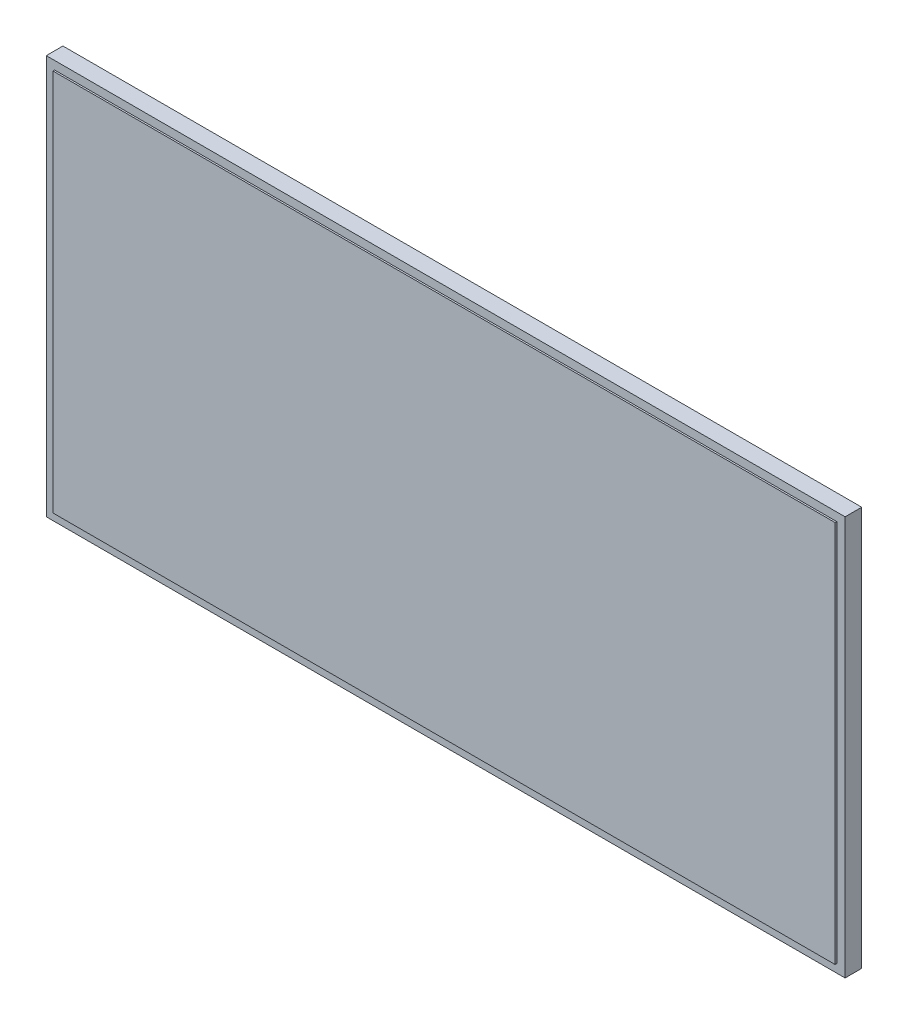
SolidWorks part; units mm, degrees
ref_plane "Front Plane" through (0, 0, 0) normal (0, 0, 1) x (1, 0, 0)
ref_plane "Top Plane" through (0, 0, 0) normal (0, 1, 0) x (1, 0, 0)
ref_plane "Right Plane" through (0, 0, 0) normal (1, 0, 0) x (0, 0, -1)
sketch "Sketch1" plane through (0, 0, 0) normal (0, 0, 1) x (1, 0, 0)
  line L1 (0, 0) -> (-6096, 0)
  line L2 (0, 0) -> (0, -3048)
  line L3 (0, -3048) -> (-6096, -3048)
  line L4 (-6096, 0) -> (-6096, -3048)
  dimension "D1" = 6096
  dimension "D2" = 3048
extrude "Boss-Extrude2" add sketch "Sketch1" along normal blind 127
sketch "Sketch3" plane through (0, 0, 127) normal (0, 0, 1) x (1, 0, 0)
  line L0 (-6096, 0) -> (-6096, -3048) construction
  line L1 (-63.5, -63.5) -> (-6032.5, -63.5)
  line L2 (-63.5, -63.5) -> (-63.5, -2984.5)
  line L3 (-63.5, -2984.5) -> (-6032.5, -2984.5)
  line L4 (-6032.5, -63.5) -> (-6032.5, -2984.5)
  line L5 (0, 0) -> (-6096, 0) construction
  dimension "D1" = 2921
  dimension "D2" = 5969
  dimension "D3" = 63.5
  dimension "D4" = 63.5
extrude "Cut-Extrude1" cut sketch "Sketch3" against normal up to next
sketch "Sketch4" plane through (0, 0, 127) normal (0, 0, 1) x (1, 0, 0)
  line L1 (-6032.5, -63.5) -> (-63.5, -63.5)
  line L2 (-6032.5, -63.5) -> (-6032.5, -2984.5)
  line L3 (-6032.5, -2984.5) -> (-63.5, -2984.5)
  line L4 (-63.5, -63.5) -> (-63.5, -2984.5)
extrude "Boss-Extrude3" add sketch "Sketch4" along normal blind 12.7 and the other way offset from surface (139.7 mm away) 12.7 other way up to face at (-3048, -1524, 0)
